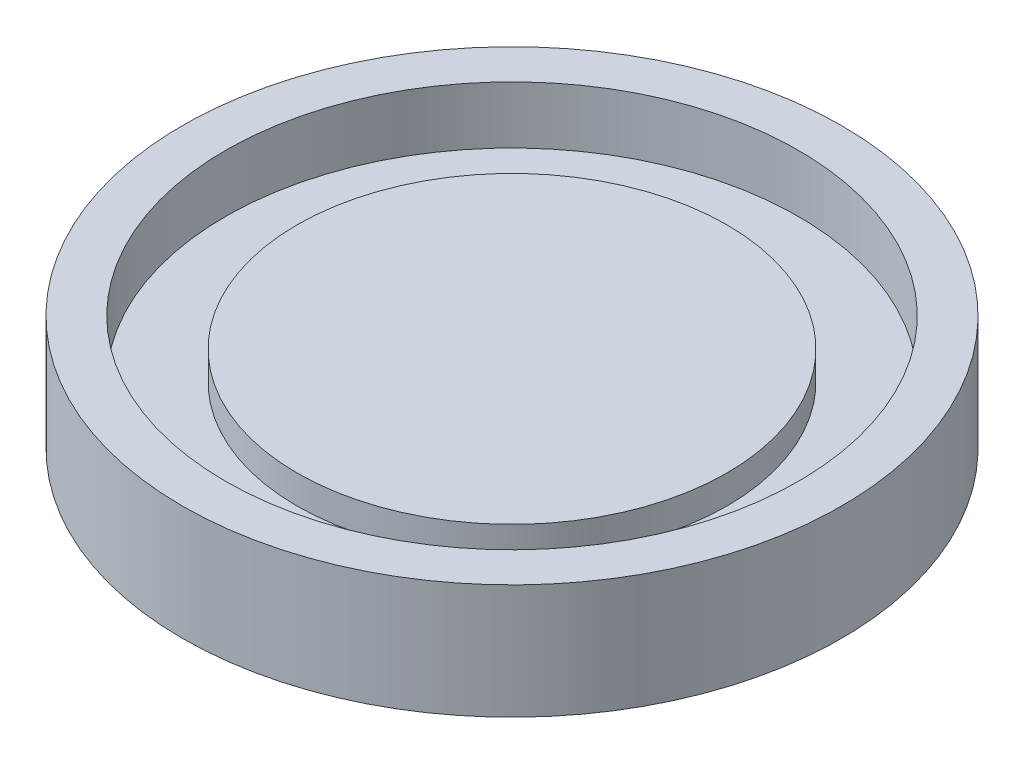
SolidWorks part; units mm, degrees
ref_plane "Front Plane" through (0, 0, 0) normal (0, 0, 1) x (1, 0, 0)
ref_plane "Top Plane" through (0, 0, 0) normal (0, 1, 0) x (1, 0, 0)
ref_plane "Right Plane" through (0, 0, 0) normal (1, 0, 0) x (0, 0, -1)
sketch "Sketch2" plane through (0, 0, 0) normal (0, 1, 0) x (1, 0, 0)
  circle A0 centre (0, 0) radius 14.605
  dimension "D1" = 29.21
extrude "Boss-Extrude2" add sketch "Sketch2" along normal blind 2.54
sketch "Sketch3" plane through (0, 2.54, 0) normal (0, 1, 0) x (1, 0, 0)
  circle A0 centre (0, 0) radius 12.7
  circle A1 centre (0, 0) radius 14.605
  dimension "D1" = 25.4
extrude "Boss-Extrude3" add sketch "Sketch3" along normal blind 2.54
sketch "Sketch4" plane through (0, 2.54, 0) normal (0, 1, 0) x (1, 0, 0)
  circle A0 centre (0, 0) radius 9.525
  dimension "D1" = 19.05
extrude "Boss-Extrude4" add sketch "Sketch4" along normal blind 1.27 contours A0
